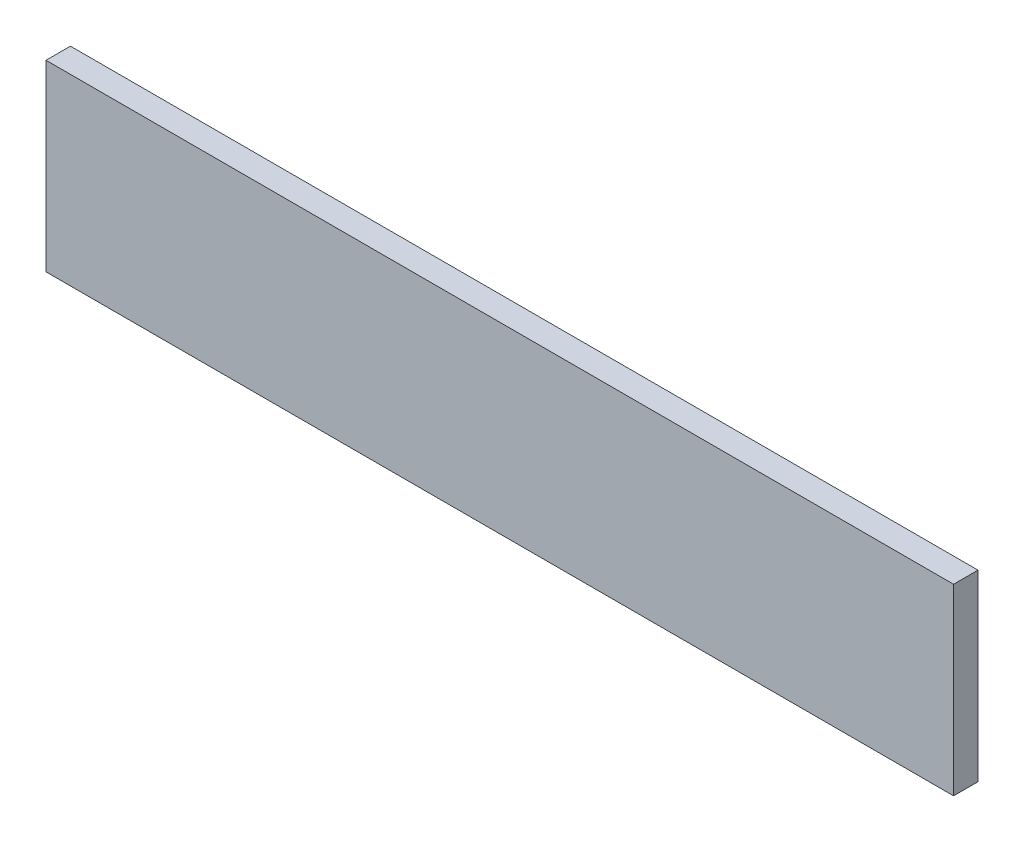
SolidWorks part; units mm, degrees
ref_plane "Front Plane" through (0, 0, 0) normal (0, 0, 1) x (1, 0, 0)
ref_plane "Top Plane" through (0, 0, 0) normal (0, 1, 0) x (1, 0, 0)
ref_plane "Right Plane" through (0, 0, 0) normal (1, 0, 0) x (0, 0, -1)
sketch "Sketch1" plane through (0, 0, 0) normal (0, 0, 1) x (1, 0, 0)
  line L0 (0, 0) -> (148.57, 0)
  line L1 (148.57, 0) -> (148.57, 30)
  line L2 (148.57, 30) -> (0, 30)
  line L3 (0, 30) -> (0, 0)
  dimension "D1" = 30
  dimension "D2" = 148.57
extrude "Boss-Extrude1" add sketch "Sketch1" along normal blind 4
